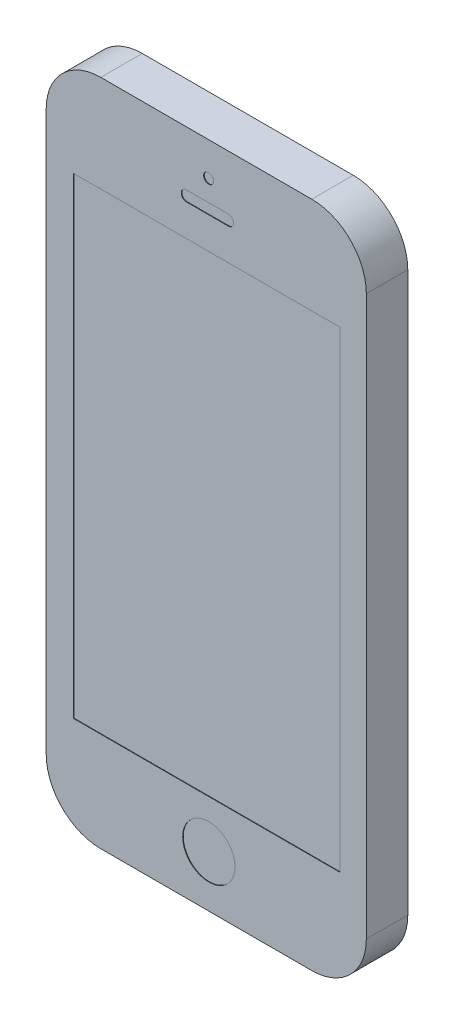
SolidWorks part; units mm, degrees
ref_plane "Front Plane" through (0, 0, 0) normal (0, 0, 1) x (1, 0, 0)
ref_plane "Top Plane" through (0, 0, 0) normal (0, 1, 0) x (1, 0, 0)
ref_plane "Right Plane" through (0, 0, 0) normal (1, 0, 0) x (0, 0, -1)
sketch "Sketch1" plane through (0, 0, 0) normal (0, 0, 1) x (1, 0, 0)
  line L0 (45.6667, 287.5) -> (228.3333, 287.5) construction
  line L1 (25.7159, 111.4923) -> (33.3916, 111.4923) construction
  line L2 (10, 122.4578) -> (48.6799, 122.4578)
  line L3 (0, 112.4578) -> (0, 10)
  line L4 (10, 0) -> (48.6799, 0)
  line L5 (58.6799, 112.4578) -> (58.6799, 10)
  line L6 (25.7159, 112.4486) -> (33.3916, 112.4486)
  line L7 (25.7159, 110.5361) -> (33.3916, 110.5361)
  line L9 (5.029, 104.7174) -> (53.829, 104.7174)
  line L10 (5.029, 104.7174) -> (5.029, 18.1815)
  line L11 (5.029, 18.1815) -> (53.829, 18.1815)
  line L12 (53.829, 104.7174) -> (53.829, 18.1815)
  arc A0 (0, 10) -> (10, 0) centre (10, 10) ccw
  arc A1 (48.6799, 0) -> (58.6799, 10) centre (48.6799, 10) ccw
  arc A2 (48.6799, 122.4578) -> (58.6799, 112.4578) centre (48.6799, 112.4578) cw
  arc A3 (10, 122.4578) -> (0, 112.4578) centre (10, 112.4578) ccw
  circle A4 centre (29.8144, 9.4163) radius 4.795
  arc A5 (25.7159, 112.4486) -> (25.7159, 110.5361) centre (25.7159, 111.4923) ccw
  arc A6 (33.3916, 110.5361) -> (33.3916, 112.4486) centre (33.3916, 111.4923) ccw
  circle A7 centre (29.7797, 116.3142) radius 0.9152
  point P18 (29.5538, 111.4923)
  dimension "D1" = 10
extrude "Boss-Extrude1" add sketch "Sketch1" along normal blind 7.6
sketch "Sketch3" plane through (0, 0, 0) normal (0, 0, -1) x (-1, 0, 0)
  line L8 (-5.029, 18.1815) -> (-5.029, 104.7174)
  line L9 (-53.829, 18.1815) -> (-5.029, 18.1815)
  line L12 (-25.7159, 112.4486) -> (-33.3916, 112.4486)
  line L13 (-33.3916, 110.5361) -> (-25.7159, 110.5361)
  line L14 (-25.7159, 112.4486) -> (-33.3916, 112.4486)
  line L15 (-33.3916, 110.5361) -> (-25.7159, 110.5361)
  line L24 (-53.829, 104.7174) -> (-53.829, 18.1815)
  line L25 (-5.029, 104.7174) -> (-53.829, 104.7174)
  line L26 (-5.029, 18.1815) -> (-5.029, 104.7174)
  line L27 (-53.829, 18.1815) -> (-5.029, 18.1815)
  line L28 (-53.829, 104.7174) -> (-53.829, 18.1815)
  line L29 (-5.029, 104.7174) -> (-53.829, 104.7174)
  circle A10 centre (-29.7797, 116.3142) radius 0.9152
  circle A11 centre (-29.7797, 116.3142) radius 0.9152
  arc A15 (-33.3916, 112.4486) -> (-33.3916, 110.5361) centre (-33.3916, 111.4923) ccw
  arc A16 (-25.7159, 110.5361) -> (-25.7159, 112.4486) centre (-25.7159, 111.4923) ccw
  arc A17 (-33.3916, 112.4486) -> (-33.3916, 110.5361) centre (-33.3916, 111.4923) ccw
  arc A18 (-25.7159, 110.5361) -> (-25.7159, 112.4486) centre (-25.7159, 111.4923) ccw
  circle A19 centre (-29.8144, 9.4163) radius 4.795
  circle A20 centre (-29.8144, 9.4163) radius 4.795
  dimension "D1" = 0
  dimension "D2" = 0
  dimension "D3" = 0
  dimension "D4" = 0
extrude "Boss-Extrude2" add sketch "Sketch3" against normal blind 7.5 separate body
